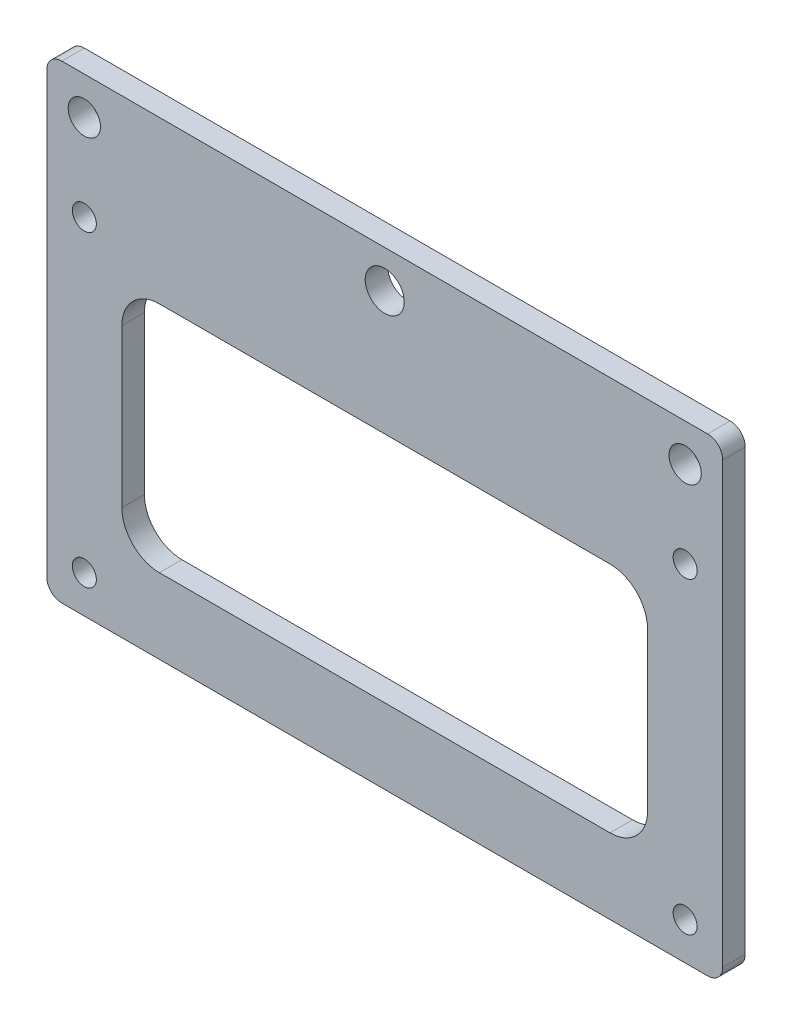
SolidWorks part; units mm, degrees
material "5052-H34"
ref_plane "正面" through (0, 0, 0) normal (0, 0, 1) x (1, 0, 0)
ref_plane "平面" through (0, 0, 0) normal (0, 1, 0) x (1, 0, 0)
ref_plane "右側面" through (0, 0, 0) normal (1, 0, 0) x (0, 0, -1)
sketch "ｽｹｯﾁ1" plane through (0, 0, 0) normal (0, 0, 1) x (1, 0, 0)
  line L0 (0, 20.5) -> (0, 0) construction
  line L1 (-40, 20.5) -> (40, 20.5) construction
  line L2 (-40, 20.5) -> (-40, -20.5) construction
  line L3 (-40, -20.5) -> (40, -20.5) construction
  line L4 (40, 20.5) -> (40, -20.5) construction
  line L5 (-40, 20.5) -> (40, -20.5) construction
  line L6 (-40, -20.5) -> (40, 20.5) construction
  line L7 (0, 0) -> (40, 0) construction
  line L8 (-40, 32) -> (40, 32) construction
  line L9 (-45, 25.5) -> (45, 25.5) construction
  line L10 (-45, 25.5) -> (-45, -25.5) construction
  line L11 (-45, -25.5) -> (45, -25.5) construction
  line L12 (45, 25.5) -> (45, -25.5) construction
  line L13 (-45, 25.5) -> (45, -25.5) construction
  line L14 (-45, -25.5) -> (45, 25.5) construction
  line L15 (-45, 37) -> (45, 37)
  line L16 (-45, 37) -> (-45, -25.5)
  line L17 (-45, -25.5) -> (45, -25.5)
  line L18 (45, 37) -> (45, -25.5)
  line L19 (-45, 37) -> (45, -25.5) construction
  line L20 (-45, -25.5) -> (45, 37) construction
  line L21 (35, 15.5) -> (-35, 15.5)
  line L22 (35, 15.5) -> (35, -15.5)
  line L23 (35, -15.5) -> (-35, -15.5)
  line L24 (-35, 15.5) -> (-35, -15.5)
  line L25 (35, 15.5) -> (-35, -15.5) construction
  line L26 (35, -15.5) -> (-35, 15.5) construction
  circle A0 centre (40, 20.5) radius 1.6
  circle A1 centre (40, 32) radius 2.15
  circle A2 centre (-40, 32) radius 2.15
  circle A3 centre (40, -20.5) radius 1.6
  circle A4 centre (-40, 20.5) radius 1.6
  circle A5 centre (-40, -20.5) radius 1.6
  circle A6 centre (0, 32) radius 2.6
  point P0 (0, 0)
  point P21 (0, 5.75)
  dimension "D3" = 3.2
  dimension "D7" = 4.3
  dimension "D12" = 5.2
  dimension "D1" = 80
  dimension "D2" = 41
  dimension "D4" = 51
  dimension "D5" = 90
  dimension "D6" = 6.5
  dimension "D8" = 80
  dimension "D9" = 5
  dimension "D10" = 5
  dimension "D11" = 5
extrude "ﾎﾞｽ - 押し出し1" add sketch "ｽｹｯﾁ1" along normal blind 3
fillet "ﾌｨﾚｯﾄ1" radius 5 4 edges at (35, 15.5, 1.5) (35, -15.5, 1.5) (-35, -15.5, 1.5) (-35, 15.5, 1.5)
fillet "ﾌｨﾚｯﾄ2" radius 2 4 edges at (-45, -25.5, 1.5) (45, -25.5, 1.5) (45, 37, 1.5) (-45, 37, 1.5)
